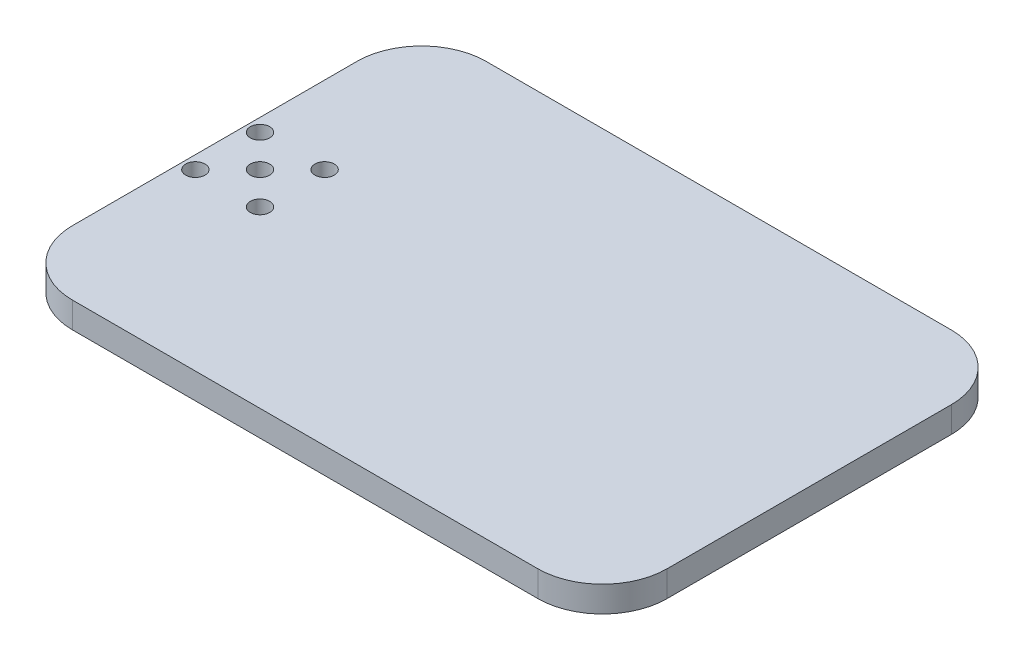
SolidWorks part; units mm, degrees
ref_plane "Front" through (0, 0, 0) normal (0, 0, 1) x (1, 0, 0)
ref_plane "Top" through (0, 0, 0) normal (0, 1, 0) x (1, 0, 0)
ref_plane "Right" through (0, 0, 0) normal (1, 0, 0) x (0, 0, -1)
sketch "Sketch1" plane through (0, 0, 0) normal (0, 1, 0) x (1, 0, 0)
  line L1 (5, 0) -> (41, 0)
  line L2 (0, 5) -> (0, 27)
  line L3 (5, 32) -> (41, 32)
  line L4 (46, 5) -> (46, 27)
  arc A0 (5, 0) -> (0, 5) centre (5, 5) cw
  arc A1 (41, 0) -> (46, 5) centre (41, 5) ccw
  arc A2 (41, 32) -> (46, 27) centre (41, 27) cw
  arc A3 (0, 27) -> (5, 32) centre (5, 27) cw
  point P7 (0, 0)
  point P10 (46, 0)
  point P13 (46, 32)
  point P16 (0, 32)
  dimension "D3" = 5
  dimension "D1" = 32
  dimension "D2" = 46
extrude "Boss-Extrude1" add sketch "Sketch1" along normal blind 2
sketch "Sketch4" plane through (46, 0, 0) normal (1, 0, 0) x (0, 0, -1)
  line L0 (5, 0) -> (27, 0) construction
  line L1 (7, 0) -> (25, 0)
  line L2 (6, 1) -> (6, 7)
  line L3 (7, 8) -> (25, 8)
  line L4 (26, 1) -> (26, 7)
  line L5 (5, 2) -> (27, 2) construction
  arc A0 (7, 0) -> (6, 1) centre (7, 1) cw
  arc A1 (25, 0) -> (26, 1) centre (25, 1) ccw
  arc A2 (25, 8) -> (26, 7) centre (25, 7) cw
  arc A3 (6, 7) -> (7, 8) centre (7, 7) cw
  point P6 (16, 2)
  point P11 (6, 0)
  point P14 (26, 0)
  point P17 (26, 8)
  point P20 (6, 8)
  dimension "D4" = 1
  dimension "D1" = 8
  dimension "D2" = 20
  dimension "D3" = 10
extrude "Boss-Extrude3" [suppressed] add sketch "Sketch4" along normal blind 2
sketch "Sketch5" [suppressed] plane through (0, 2, 0) normal (0, 1, 0) x (1, 0, 0)
  line L0 (46, 6) -> (46, 26) construction
  line L1 (46, 22) -> (44, 22)
  line L2 (46, 22) -> (46, 21.2889)
  line L3 (46, 21.2889) -> (44, 21.2889)
  line L4 (44, 22) -> (44, 21.2889)
  line L5 (46, 20) -> (46, 19.2889)
  line L6 (46, 20) -> (44, 20)
  line L7 (44, 20) -> (44, 19.2889)
  line L8 (46, 19.2889) -> (44, 19.2889)
  line L9 (46, 18) -> (46, 17.2889)
  line L10 (46, 18) -> (44, 18)
  line L11 (44, 18) -> (44, 17.2889)
  line L12 (46, 17.2889) -> (44, 17.2889)
  line L13 (46, 16) -> (46, 15.2889)
  line L14 (46, 16) -> (44, 16)
  line L15 (44, 16) -> (44, 15.2889)
  line L16 (46, 15.2889) -> (44, 15.2889)
  line L17 (46, 14) -> (46, 13.2889)
  line L18 (46, 14) -> (44, 14)
  line L19 (44, 14) -> (44, 13.2889)
  line L20 (46, 13.2889) -> (44, 13.2889)
  line L21 (46, 12) -> (46, 11.2889)
  line L22 (46, 12) -> (44, 12)
  line L23 (44, 12) -> (44, 11.2889)
  line L24 (46, 11.2889) -> (44, 11.2889)
  dimension "D2" = 2
  dimension "D3" = 4
  dimension "D1" = 6
extrude "Boss-Extrude4" [suppressed] add sketch "Sketch5" along normal blind 0.1
sketch "Sketch6" [suppressed] plane through (46, 0, 0) normal (-1, 0, 0) x (0, 0, 1)
  line L0 (-20, 2.1) -> (-20, 4.1)
  line L1 (-22, 2.1) -> (-21.2889, 2.1)
  line L2 (-22, 2.1) -> (-22, 4.1)
  line L3 (-22, 4.1) -> (-21.2889, 4.1)
  line L4 (-21.2889, 2.1) -> (-21.2889, 4.1)
  line L5 (-20, 4.1) -> (-19.2889, 4.1)
  line L6 (-19.2889, 2.1) -> (-19.2889, 4.1)
  line L7 (-20, 2.1) -> (-19.2889, 2.1)
  line L8 (-18, 2.1) -> (-18, 4.1)
  line L9 (-18, 4.1) -> (-17.2889, 4.1)
  line L10 (-17.2889, 2.1) -> (-17.2889, 4.1)
  line L11 (-18, 2.1) -> (-17.2889, 2.1)
  line L12 (-16, 2.1) -> (-16, 4.1)
  line L13 (-16, 4.1) -> (-15.2889, 4.1)
  line L14 (-15.2889, 2.1) -> (-15.2889, 4.1)
  line L15 (-16, 2.1) -> (-15.2889, 2.1)
  line L16 (-14, 2.1) -> (-14, 4.1)
  line L17 (-14, 4.1) -> (-13.2889, 4.1)
  line L18 (-13.2889, 2.1) -> (-13.2889, 4.1)
  line L19 (-14, 2.1) -> (-13.2889, 2.1)
  line L20 (-12, 2.1) -> (-12, 4.1)
  line L21 (-12, 4.1) -> (-11.2889, 4.1)
  line L22 (-11.2889, 2.1) -> (-11.2889, 4.1)
  line L23 (-12, 2.1) -> (-11.2889, 2.1)
  dimension "D1" = 2
  dimension "D2" = 6
extrude "Boss-Extrude5" [suppressed] add sketch "Sketch6" along normal blind 0.1
sketch "Sketch8" plane through (0, 2, 0) normal (0, 1, 0) x (1, 0, 0)
  line L0 (41, 32) -> (5, 32) construction
  line L1 (0, 27) -> (0, 5) construction
  circle A0 centre (3.5, 16) radius 0.75
  circle A1 centre (6, 18.5) radius 0.75
  circle A2 centre (6, 13.5) radius 0.75
  circle A3 centre (1, 13.5) radius 0.75
  circle A4 centre (1, 18.5) radius 0.75
  point P10 (0, 0)
  dimension "D1" = 1.5
  dimension "D2" = 1.5
  dimension "D3" = 1.5
  dimension "D4" = 1.5
  dimension "D5" = 1.5
  dimension "D6" = 5
  dimension "D7" = 5
  dimension "D8" = 5
  dimension "D9" = 5
  dimension "D10" = 2.5
  dimension "D11" = 2.5
  dimension "D12" = 16
  dimension "D13" = 3.5
extrude "Cut-Extrude2" cut sketch "Sketch8" against normal up to next
